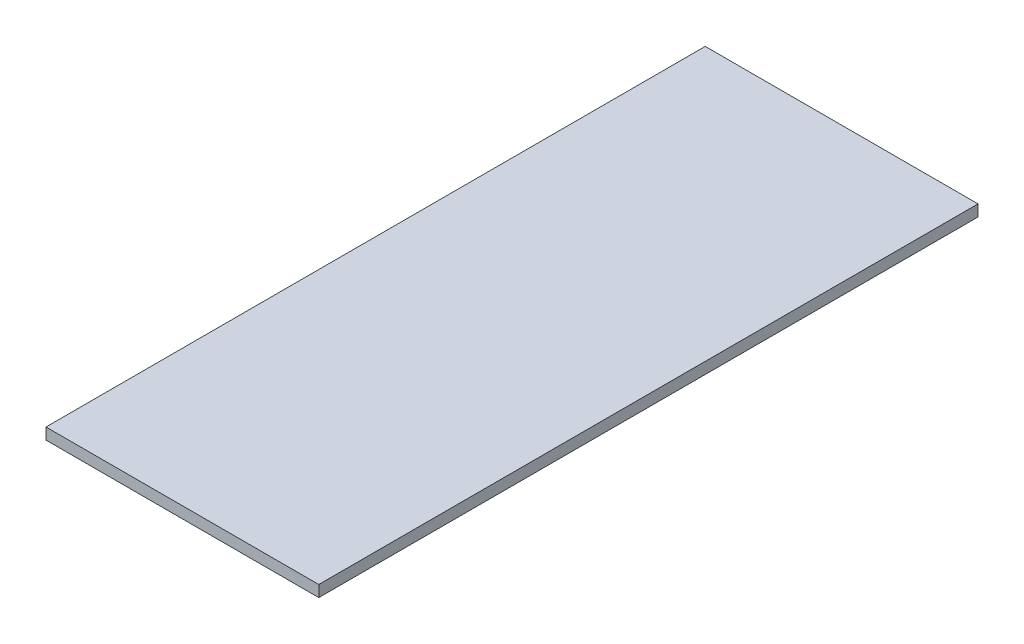
SolidWorks part; units mm, degrees
ref_plane "Ebene vorne" through (0, 0, 0) normal (0, 0, 1) x (1, 0, 0)
ref_plane "Ebene oben" through (0, 0, 0) normal (0, 1, 0) x (1, 0, 0)
ref_plane "Ebene rechts" through (0, 0, 0) normal (1, 0, 0) x (0, 0, -1)
sketch "Skizze1" plane through (0, 0, 0) normal (0, 1, 0) x (1, 0, 0)
  line L1 (-60, -145) -> (60, -145)
  line L2 (-60, -145) -> (-60, 145)
  line L3 (-60, 145) -> (60, 145)
  line L4 (60, -145) -> (60, 145)
  line L5 (-60, -145) -> (60, 145) construction
  line L6 (-60, 145) -> (60, -145) construction
  point P0 (0, 0)
  dimension "D1" = 120
  dimension "D2" = 290
extrude "Aufsatz-Linear austragen1" add sketch "Skizze1" along normal blind 5
